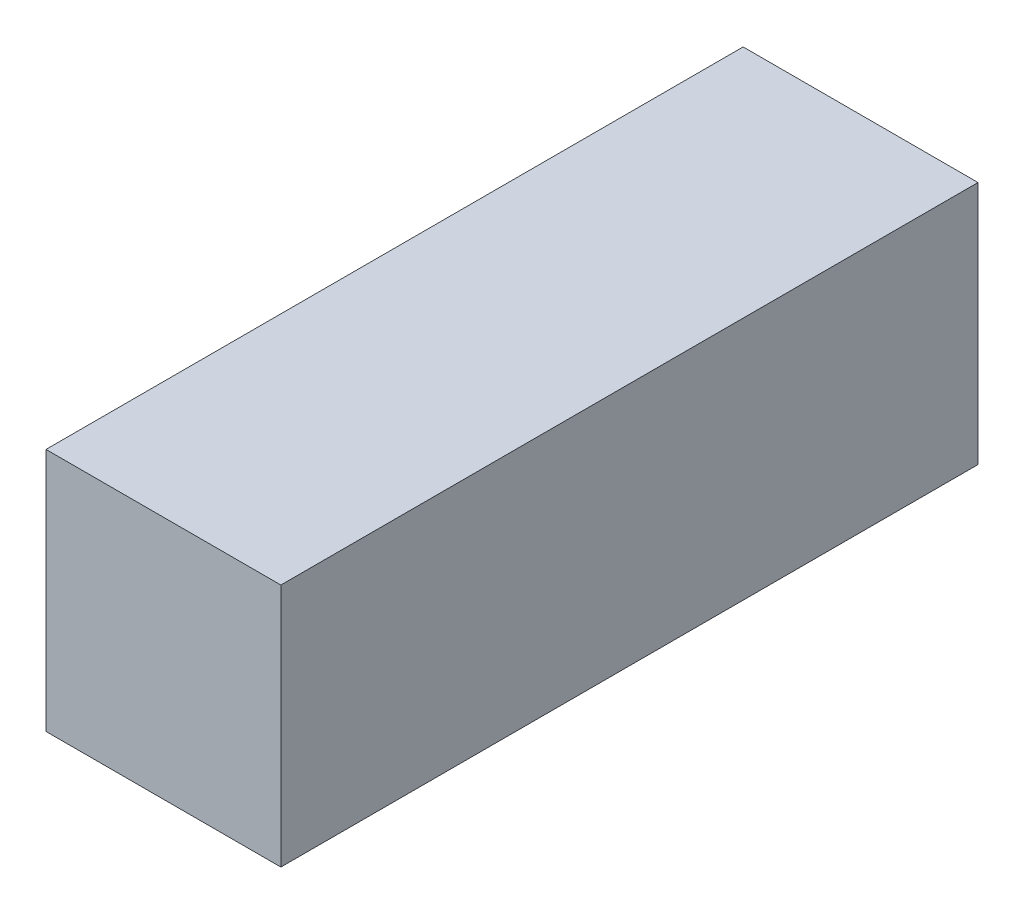
SolidWorks part; units mm, degrees
ref_plane "Front Plane" through (0, 0, 0) normal (0, 0, 1) x (1, 0, 0)
ref_plane "Top Plane" through (0, 0, 0) normal (0, 1, 0) x (1, 0, 0)
ref_plane "Right Plane" through (0, 0, 0) normal (1, 0, 0) x (0, 0, -1)
sketch "Sketch1" plane through (0, 0, 0) normal (0, 0, 1) x (1, 0, 0)
  circle A0 centre (0, 0) radius 457.2
sketch "Sketch2" plane through (0, 0, 0) normal (1, 0, 0) x (0, 0, -1)
  line L0 (-1371.6, 0) -> (1371.6, 0)
  line L1 (502.92, 0) -> (-502.92, 0) construction
  line L2 (0, 457.2) -> (0, -457.2) construction
  spline S0 degree 3 poles (-1371.6, 0) (-1157.2865, 494.8545) (-443.0292, 487.5286) (0, 457.2) knots 0 0 0 0 1 1 1 1
  spline S1 degree 2 poles (0, 457.2) (754.1724, 374.0587) (1371.6, 0) knots 0 0 0 0.947102 0.947102 0.947102
revolve "Revolve1" add sketch "Sketch2" angle 360 about L0
ref_plane "Plane1" through (0, 0, 1460) normal (0, 0, 1) x (1, 0, 0)
sketch "Sketch3" plane through (0, 0, 1460) normal (0, 0, 1) x (1, 0, 0)
  line L1 (-513.4125, -534.0311) -> (513.4125, -534.0311)
  line L2 (-513.4125, -534.0311) -> (-513.4125, 534.0311)
  line L3 (-513.4125, 534.0311) -> (513.4125, 534.0311)
  line L4 (513.4125, -534.0311) -> (513.4125, 534.0311)
  line L5 (-513.4125, -534.0311) -> (513.4125, 534.0311) construction
  line L6 (-513.4125, 534.0311) -> (513.4125, -534.0311) construction
  point P0 (0, 0)
extrude "Boss-Extrude2" add sketch "Sketch3" against normal blind 3048 separate body contours L3 L4 L1 L2
combine bodies "Combine1" operation type subtract main body 103 bodies to subtract 101
